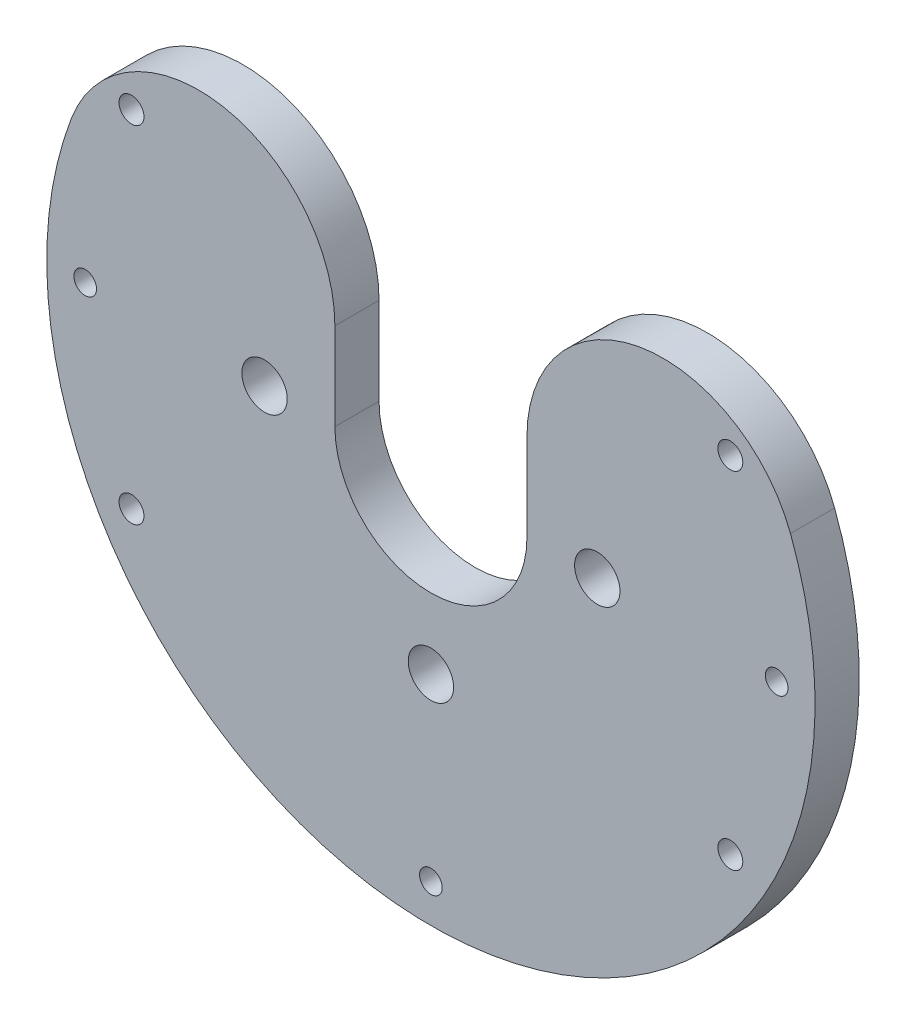
SolidWorks part; units mm, degrees
material "Acrylic (Medium-high impact)"
ref_plane "Front Plane" through (0, 0, 0) normal (0, 0, 1) x (1, 0, 0)
ref_plane "Top Plane" through (0, 0, 0) normal (0, 1, 0) x (1, 0, 0)
ref_plane "Right Plane" through (0, 0, 0) normal (1, 0, 0) x (0, 0, -1)
sketch "Sketch1" plane through (0, 0, 0) normal (0, 0, 1) x (1, 0, 0)
  line L0 (0, 76.2) -> (0, -50.8) construction
  line L1 (-50.8, 0) -> (-12.7, 0) construction
  line L2 (12.7, 0) -> (22, 0) construction
  line L3 (0, 0) -> (-45.72, 0) construction
  line L4 (-12.7, 0) -> (-12.7, 49.1869)
  line L5 (12.7, 0) -> (12.7, 49.1869)
  line L6 (12.7, 0) -> (50.8, 0) construction
  arc A0 (-12.7, 49.1869) -> (12.7, 49.1869) centre (0, 0) ccw
  arc A1 (-12.7, 0) -> (12.7, 0) centre (0, 0) ccw
  circle A2 centre (22, 0) radius 3
  circle A3 centre (0, -22) radius 3
  circle A4 centre (-22, 0) radius 3
  circle A5 centre (0, 22) radius 3 [skipped]
  circle A6 centre (-45.72, 0) radius 1.5
  circle A7 centre (0, 45.72) radius 1.5 [skipped]
  circle A8 centre (45.72, 0) radius 1.5
  circle A9 centre (0, -45.72) radius 1.5
  circle A10 centre (0, 45.72) radius 1.65 construction
  circle A11 centre (39.5947, 22.86) radius 1.65
  circle A12 centre (39.5947, -22.86) radius 1.65
  circle A13 centre (0, -45.72) radius 1.65 construction
  circle A14 centre (-39.5947, -22.86) radius 1.65
  circle A15 centre (-39.5947, 22.86) radius 1.65
  point P20 (0, 0)
  point P29 (0, 0)
  point P39 (0, 0)
  point P41 (0, 0)
  dimension "D1" = 101.6
  dimension "D2" = 25.4
  dimension "D4" = 4
  dimension "D5" = 6
  dimension "D7" = 4
  dimension "D8" = 3
  dimension "D9" = 45.72
  dimension "D10" = 3.3
  dimension "D3" = 22
  dimension "D6" = 45.72
  dimension "D11" = 6
extrude "Boss-Extrude1" add sketch "Sketch1" along normal blind 5.842 contours A1 L4 A0 L5 A14 A13 A12 A11 A9 A8 A6 A4 A3 A2
fillet "Fillet1" radius 18 2 edges at (12.7, 49.1869, 2.921) (-12.7, 49.1869, 2.921)
